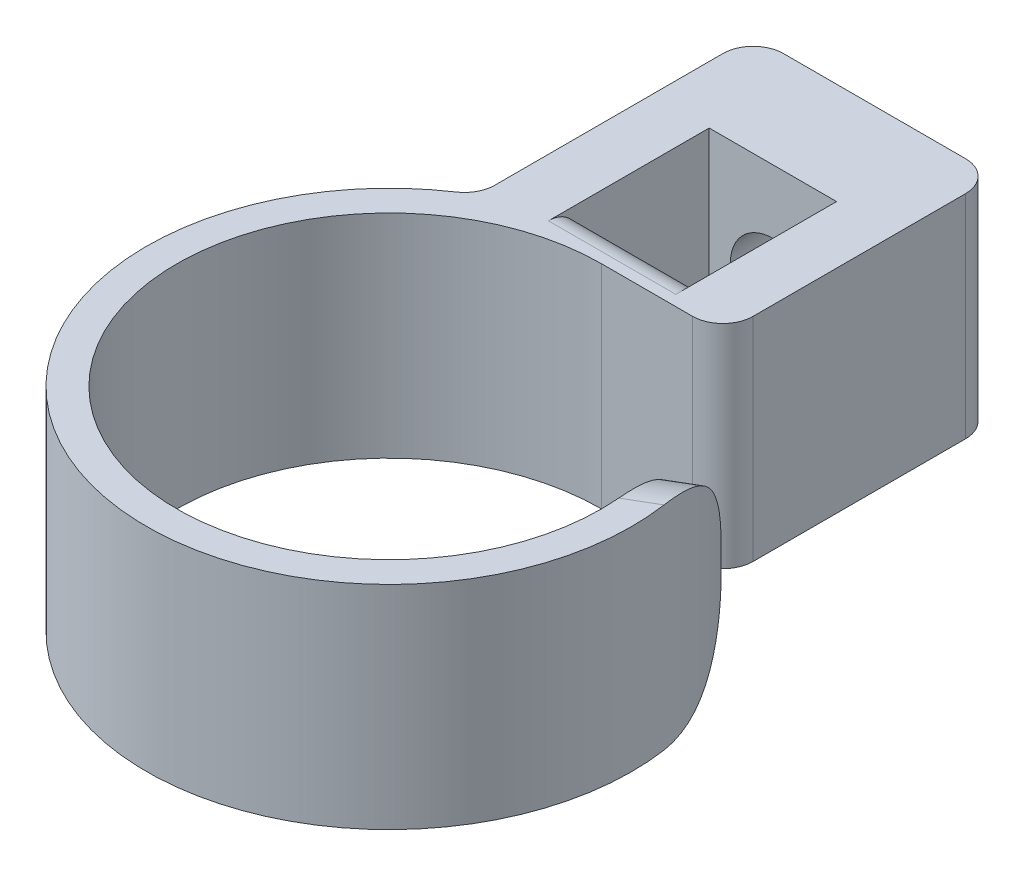
SolidWorks part; units mm, degrees
ref_plane "前视基准面" through (0, 0, 0) normal (0, 0, 1) x (1, 0, 0)
ref_plane "上视基准面" through (0, 0, 0) normal (0, 1, 0) x (1, 0, 0)
ref_plane "右视基准面" through (0, 0, 0) normal (1, 0, 0) x (0, 0, -1)
other "Configuration Table"
sketch "Sketch1" plane through (0, 0, 0) normal (0, 1, 0) x (1, 0, 0)
  line L0 (0, 0) -> (0, 7)
  line L1 (-4, 7) -> (-3.873, 7)
  line L2 (0, 7) -> (0, 14) construction
  line L3 (-4, 7) -> (-3.873, 7)
  line L4 (-4, 7) -> (-4, 14)
  line L5 (-4, 14) -> (4, 14)
  line L6 (4, 7) -> (4, 14)
  line L7 (-4, 10.5) -> (4, 10.5) construction
  line L8 (4, 7) -> (0, 0)
  line L9 (-2.1, 12.65) -> (2.1, 12.65)
  line L10 (-2.1, 12.65) -> (-2.1, 8.35)
  line L11 (-2.1, 8.35) -> (2.1, 8.35)
  line L12 (2.1, 12.65) -> (2.1, 8.35)
  line L13 (-2.1, 12.65) -> (2.1, 8.35) construction
  line L14 (-2.1, 8.35) -> (2.1, 12.65) construction
  line L15 (0, 0) -> (6.9103, 4.0308)
  line L16 (-4, 7) -> (-4, 6.9282)
  line L17 (0, 7) -> (4, 7)
  line L18 (0, 7) -> (4, 7)
  circle A0 centre (0, 0) radius 7
  arc A1 (-3.873, 7) -> (3.873, 7) centre (0, 0) ccw
  point P8 (0, 7)
  point P13 (0, 10.5)
  dimension "D1" = 14
  dimension "D2" = 16
  dimension "D3" = 8
  dimension "D4" = 7
  dimension "D5" = 4.2
  dimension "D6" = 4.3
  dimension "D7" = 30
extrude "Boss-Extrude1" add sketch "Sketch1" along normal blind 7 contours L1 A1 L15 A0 L17 L18 L6 L5 L4 L9 L12 L11 L10 | A1 L1 L16
fillet "Fillet1" radius 1 2 edges at (4, 3.5, -7) (-4, 3.5, -6.9282)
fillet "Fillet2" radius 3 2 edges at (6.4784, 0, -3.7789) (6.4784, 7, -3.7789)
fillet "Fillet3" radius 1 2 edges at (0, 7, -8.35) (0, 0, -8.35)
sketch "Sketch3" plane through (0, 0, -14) normal (0, 0, -1) x (-1, 0, 0)
  line L1 (-4, 7) -> (4, 7)
  line L2 (-4, 7) -> (-4, 0)
  line L3 (-4, 0) -> (4, 0)
  line L4 (4, 7) -> (4, 0)
extrude "Boss-Extrude2" add sketch "Sketch3" along normal blind 2
sketch "Sketch2" plane through (0, 0, -16) normal (0, 0, -1) x (-1, 0, 0)
  line L0 (0, 2.1) -> (0, 4.9) construction
  circle A0 centre (0, 3.5) radius 1.4
  dimension "D1" = 2.8
extrude "Cut-Extrude2" cut sketch "Sketch2" against normal blind 4
fillet "Fillet4" radius 1 2 edges at (-4, 3.5, -16) (4, 3.5, -16)
